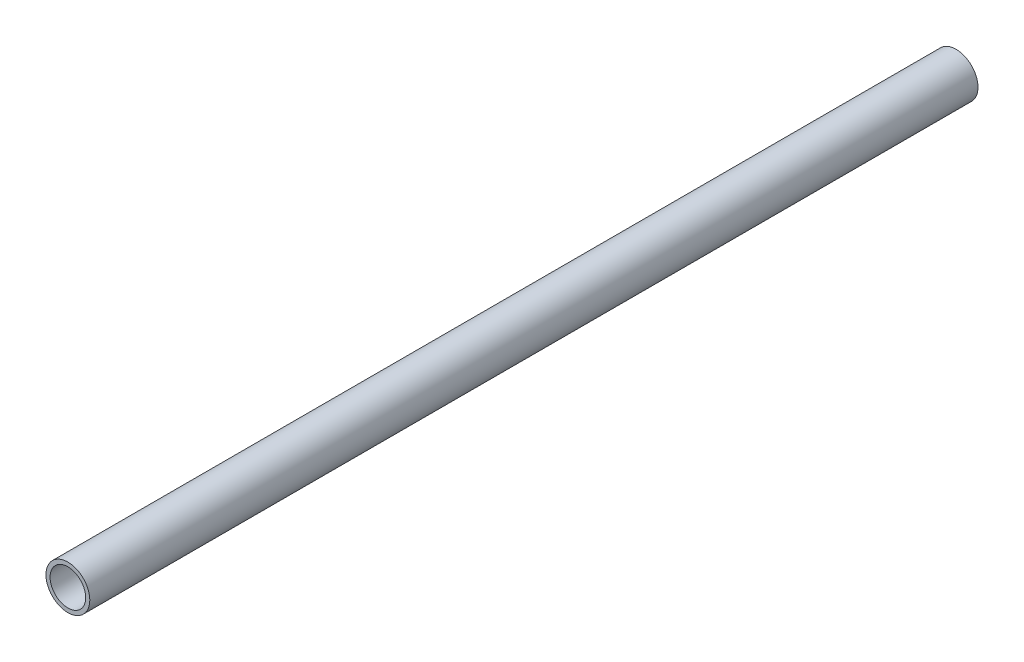
SolidWorks part; units mm, degrees
material "AISI 316 Annealed Stainless Steel Bar (SS)"
ref_plane "Front Plane" through (0, 0, 0) normal (0, 0, 1) x (1, 0, 0)
ref_plane "Top Plane" through (0, 0, 0) normal (0, 1, 0) x (1, 0, 0)
ref_plane "Right Plane" through (0, 0, 0) normal (1, 0, 0) x (0, 0, -1)
sketch "Sketch1" plane through (0, 0, 0) normal (0, 0, 1) x (1, 0, 0)
  circle A0 centre (0, 0) radius 4.7625
  circle A1 centre (0, 0) radius 3.8735
  dimension "D1" = 9.525
  dimension "D2" = 7.747
  dimension "D3" = 0.889
extrude "Boss-Extrude1" add sketch "Sketch1" along normal blind 193
